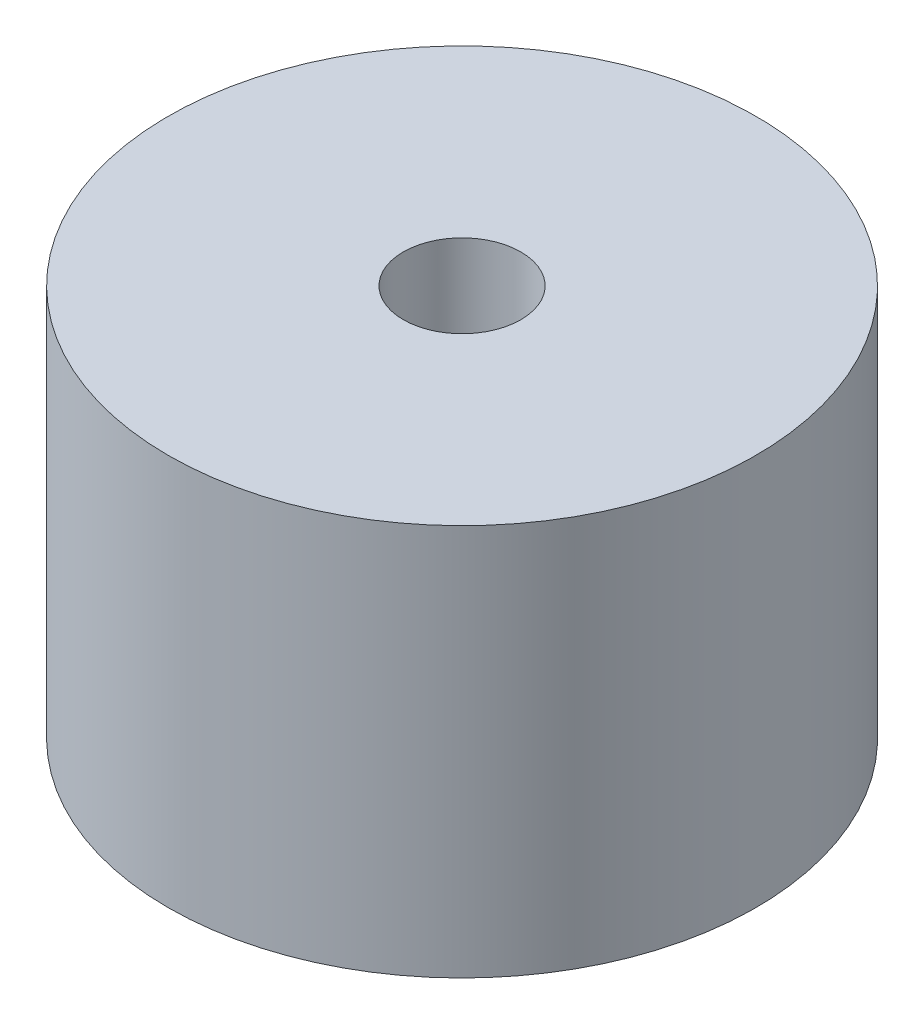
SolidWorks part; units mm, degrees
ref_plane "Plan de face" through (0, 0, 0) normal (0, 0, 1) x (1, 0, 0)
ref_plane "Plan de dessus" through (0, 0, 0) normal (0, 1, 0) x (1, 0, 0)
ref_plane "Plan de droite" through (0, 0, 0) normal (1, 0, 0) x (0, 0, -1)
sketch "Esquisse1" plane through (0, 0, 0) normal (0, 1, 0) x (1, 0, 0)
  circle A0 centre (0, 0) radius 15
  dimension "D1" = 30
extrude "Boss.-Extru.1" add sketch "Esquisse1" along normal blind 20
sketch "Esquisse2" plane through (0, 0, 0) normal (0, -1, 0) x (-1, 0, 0)
  circle A0 centre (0, 0) radius 10
  dimension "D1" = 20
extrude "Enlèv. mat.-Extru.1" cut sketch "Esquisse2" against normal blind 12
sketch "Esquisse3" plane through (0, 12, 0) normal (0, -1, 0) x (-1, 0, 0)
  circle A0 centre (0, 0) radius 3
  dimension "D1" = 6
extrude "Enlèv. mat.-Extru.2" cut sketch "Esquisse3" against normal blind 12
sketch "Esquisse4" plane through (0, 0, 0) normal (0, -1, 0) x (-1, 0, 0)
  circle A0 centre (-12.7, 0) radius 1.5
  circle A1 centre (0, -12.7) radius 1.5
  circle A3 centre (12.7, 0) radius 1.5
  circle A4 centre (0, 12.7) radius 1.5
  dimension "D1" = 12.7
  dimension "D2" = 12.7
  dimension "D3" = 3
  dimension "D4" = 12.7
  dimension "D5" = 12.7
extrude "Enlèv. mat.-Extru.3" cut sketch "Esquisse4" against normal blind 8
